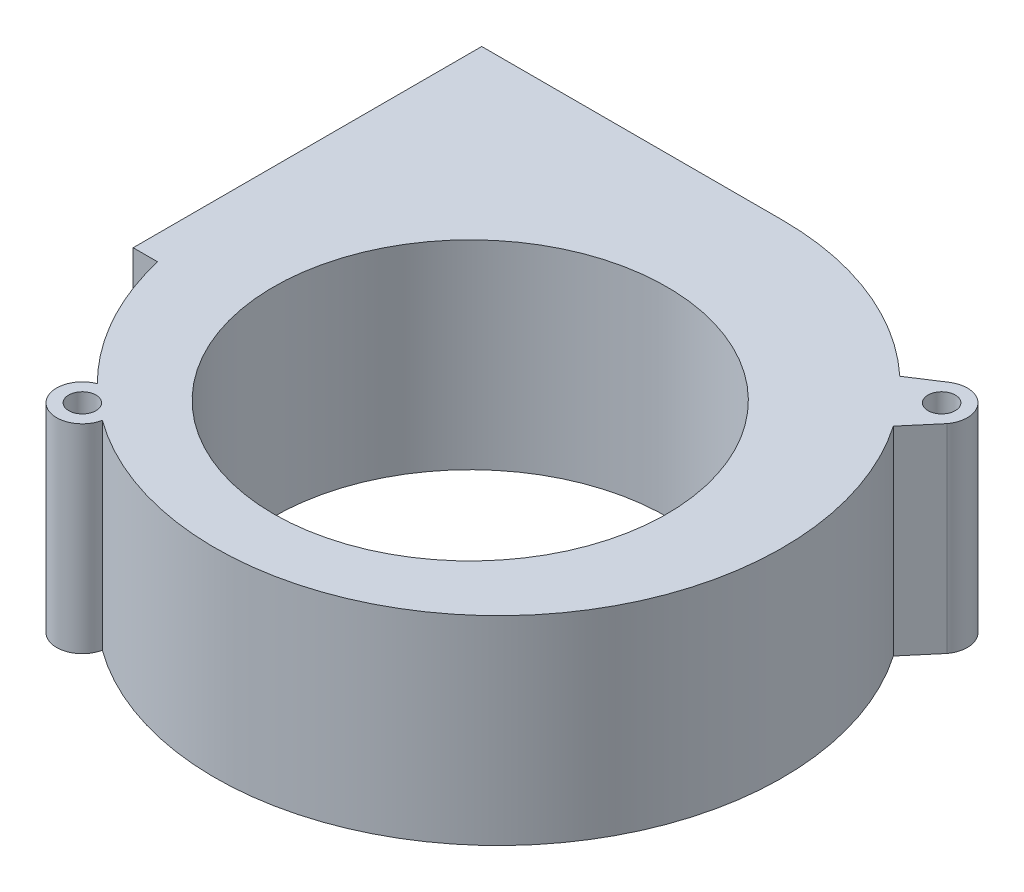
SolidWorks part; units mm, degrees
ref_plane "前视基准面" through (0, 0, 0) normal (0, 0, 1) x (1, 0, 0)
ref_plane "上视基准面" through (0, 0, 0) normal (0, 1, 0) x (1, 0, 0)
ref_plane "右视基准面" through (0, 0, 0) normal (1, 0, 0) x (0, 0, -1)
other "Configuration Table"
sketch "草图1" plane through (0, 0, 0) normal (0, 1, 0) x (1, 0, 0)
  line L0 (32.0382, 34.2515) -> (36.9852, 37.4643)
  line L1 (-49.7, 46.9) -> (0, 46.9)
  line L2 (-49.7, 46.9) -> (-49.7, -10.7)
  line L3 (-49.7, -10.7) -> (-45.6631, -10.7)
  line L5 (38.6456, 26.5731) -> (42.7161, 31.3716)
  arc A0 (-45.6631, -10.7) -> (-33.2022, -33.1243) centre (0, 0) ccw
  circle A1 centre (-31.7, -37.1) radius 2.25
  circle A2 centre (39.3, 33.9) radius 2.25
  circle A3 centre (0, -4.7) radius 32.5
  arc A4 (-33.2022, -33.1243) -> (-27.5387, -37.9636) centre (-31.7, -37.1) ccw
  arc A5 (42.7161, 31.3716) -> (36.9852, 37.4643) centre (39.3, 33.9) ccw
  arc A6 (32.0382, 34.2515) -> (0, 46.9) centre (0, 0) ccw
  circle A7 centre (-31.7, -37.1) radius 4.25 construction
  arc A8 (-27.5387, -37.9636) -> (38.6456, 26.5731) centre (0, 0) ccw
  circle A10 centre (39.3, 33.9) radius 4.25 construction
  point P16 (-27.45, -37.1)
  point P23 (43.55, 33.9)
  dimension "D1" = 93.8
  dimension "D6" = 4.5
  dimension "D7" = 4.5
  dimension "D10" = 65
  dimension "D2" = 57.6
  dimension "D3" = 46.9
  dimension "D5" = 49.7
  dimension "D8" = 31.7
  dimension "D4" = 51.6
  dimension "D9" = 32.4
  dimension "D11" = 39.3
  dimension "D12" = 38.6
  dimension "D13" = 2
  dimension "D14" = 2
extrude "凸台-拉伸1" add sketch "草图1" along normal blind 32.9
equation "\"D1@草图1\"=(96.6-49.7)*2"
equation "\"D3@草图1\"=\"D1@草图1\"/2"
